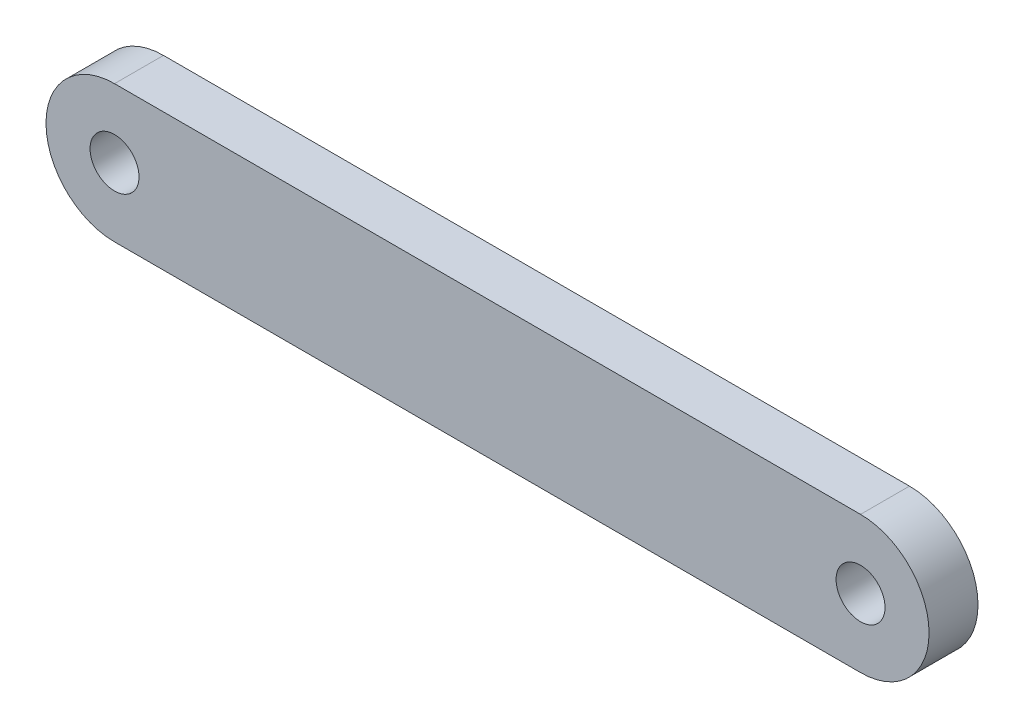
SolidWorks part; units mm, degrees
ref_plane "Front Plane" through (0, 0, 0) normal (0, 0, 1) x (1, 0, 0)
ref_plane "Top Plane" through (0, 0, 0) normal (0, 1, 0) x (1, 0, 0)
ref_plane "Right Plane" through (0, 0, 0) normal (1, 0, 0) x (0, 0, -1)
sketch "Sketch1" plane through (0, 0, 0) normal (0, 0, 1) x (1, 0, 0)
  line L0 (-49.4442, -8.7733) -> (47.3438, -8.7733)
  line L1 (-49.4442, 9.0067) -> (47.3438, 9.0067)
  line L2 (-49.4442, -8.7733) -> (47.3438, 9.0067) construction
  line L3 (-49.4442, 9.0067) -> (47.3438, -8.7733) construction
  arc A0 (-49.4442, 9.0067) -> (-49.4442, -8.7733) centre (-49.4442, 0.1167) ccw
  arc A1 (47.3438, 9.0067) -> (47.3438, -8.7733) centre (47.3438, 0.1167) cw
  circle A2 centre (-49.4442, 0.1167) radius 3.175
  circle A3 centre (47.3438, 0.1167) radius 3.175
  point P0 (-1.0502, 0.1167)
  dimension "D3" = 6.35
  dimension "D1" = 96.788
  dimension "D2" = 17.78
extrude "Boss-Extrude1" add sketch "Sketch1" along normal blind 6.35
